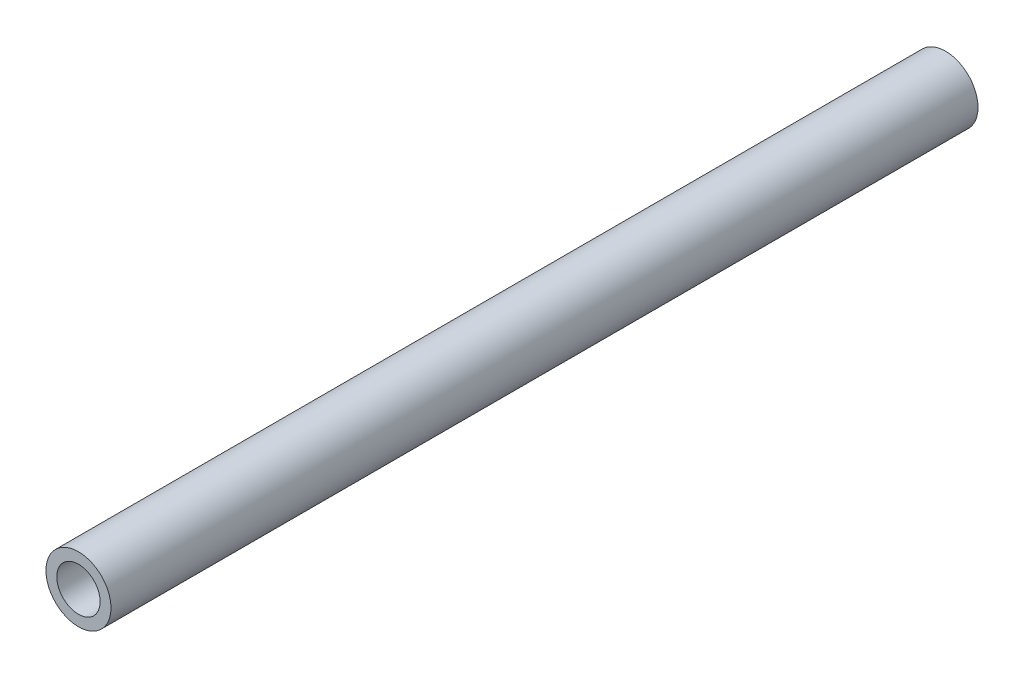
SolidWorks part; units mm, degrees
ref_plane "Front Plane" through (0, 0, 0) normal (0, 0, 1) x (1, 0, 0)
ref_plane "Top Plane" through (0, 0, 0) normal (0, 1, 0) x (1, 0, 0)
ref_plane "Right Plane" through (0, 0, 0) normal (1, 0, 0) x (0, 0, -1)
sketch "Sketch1" plane through (0, 0, 0) normal (0, 0, 1) x (1, 0, 0)
  circle A0 centre (0, 0) radius 3
  circle A1 centre (0, 0) radius 2
  dimension "D1" = 6
  dimension "D2" = 4
extrude "Boss-Extrude1" add sketch "Sketch1" along normal blind 80
